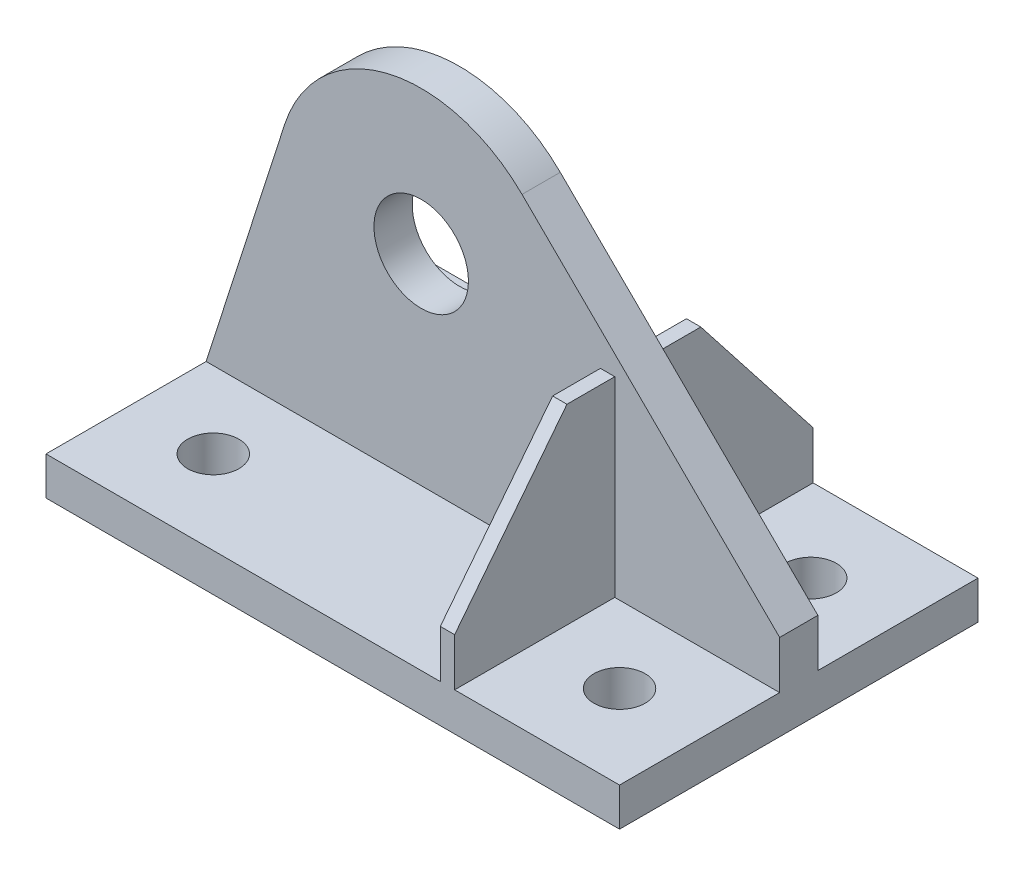
SolidWorks part; units mm, degrees
ref_plane "前视基准面" through (0, 0, 0) normal (0, 0, 1) x (1, 0, 0)
ref_plane "上视基准面" through (0, 0, 0) normal (0, 1, 0) x (1, 0, 0)
ref_plane "右视基准面" through (0, 0, 0) normal (1, 0, 0) x (0, 0, -1)
sketch "草图1" plane through (0, 0, 0) normal (0, 1, 0) x (1, 0, 0)
  line L1 (0, 0) -> (240, 0)
  line L2 (0, 0) -> (0, 150)
  line L3 (0, 150) -> (240, 150)
  line L4 (240, 0) -> (240, 150)
  dimension "D1" = 240
  dimension "D2" = 150
extrude "凸台-拉伸1" add sketch "草图1" along normal blind 16
sketch "草图2" plane through (0, 16, 0) normal (0, 1, 0) x (1, 0, 0)
  line L0 (0, 0) -> (240, 0) construction
  line L1 (0, 150) -> (0, 0) construction
  circle A0 centre (35, 35) radius 10.7283
  dimension "D1" = 35
  dimension "D2" = 35
extrude "切除-拉伸1" cut sketch "草图2" against normal through all
pattern_linear "阵列(线性)1" count 2 spacing 170 along (1, 0, 0) count 2 spacing 80 along (0, 0, -1) of "切除-拉伸1"
sketch "草图3" plane through (0, 16, 0) normal (0, 1, 0) x (1, 0, 0)
  line L0 (240, 150) -> (0, 150) construction
  line L1 (165, 150) -> (171, 150)
  line L2 (165, 150) -> (165, 0)
  line L3 (165, 0) -> (171, 0)
  line L4 (171, 150) -> (171, 0)
  line L5 (0, 0) -> (240, 0) construction
  line L6 (0, 150) -> (0, 0) construction
  dimension "D1" = 6
  dimension "D2" = 165
extrude "凸台-拉伸2" add sketch "草图3" along normal blind 80
sketch "草图4" plane through (165, 0, 0) normal (-1, 0, 0) x (0, 0, 1)
  line L0 (0, 96) -> (-47, 96)
  line L1 (-150, 96) -> (0, 96) construction
  line L2 (-47, 96) -> (0, 36)
  line L3 (0, 96) -> (0, 16) construction
  line L4 (-150, 96) -> (-103, 96)
  line L5 (-103, 96) -> (-150, 36)
  line L6 (-150, 96) -> (-150, 16) construction
  line L7 (-150, 36) -> (-150, 96)
  line L8 (0, 96) -> (0, 36)
  dimension "D1" = 60
  dimension "D2" = 47
  dimension "D3" = 60
  dimension "D4" = 47
extrude "切除-拉伸2" cut sketch "草图4" against normal through all
sketch "草图7" plane through (0, 16, 0) normal (0, 1, 0) x (1, 0, 0)
  line L0 (0, 75) -> (240, 75) construction
  line L1 (0, 150) -> (0, 0) construction
  line L2 (240, 0) -> (240, 150) construction
  line L4 (0, 83) -> (240, 83)
  line L5 (0, 83) -> (0, 67)
  line L6 (0, 67) -> (240, 67)
  line L7 (240, 83) -> (240, 67)
  dimension "D1" = 8
  dimension "D2" = 8
extrude "凸台-拉伸3" add sketch "草图7" along normal blind 144
sketch "草图12" plane through (0, 0, -67) normal (0, 0, 1) x (1, 0, 0)
  line L0 (0, 160) -> (240, 160) construction
  line L1 (0, 16) -> (165, 16) construction
  line L2 (0, 160) -> (0, 16) construction
  line L3 (32.8745, 118.3488) -> (0, 16)
  line L4 (0, 16) -> (0, 160)
  line L5 (0, 160) -> (90, 160)
  arc A0 (90, 160) -> (32.8745, 118.3488) centre (90, 100) ccw
  dimension "D3" = 60
  dimension "D1" = 84
  dimension "D2" = 90
extrude "切除-拉伸4" cut sketch "草图12" against normal through all
sketch "草图14" plane through (0, 0, -67) normal (0, 0, 1) x (1, 0, 0)
  line L0 (0, 16) -> (165, 16) construction
  line L1 (90, 160) -> (240, 160) construction
  line L2 (132.1986, 142.653) -> (240, 36)
  line L3 (240, 160) -> (240, 16) construction
  line L4 (240, 36) -> (240, 160)
  line L5 (240, 160) -> (90, 160)
  arc A0 (90, 160) -> (132.1986, 142.653) centre (90, 100) cw
  dimension "D1" = 84
  dimension "D2" = 90
  dimension "D3" = 20
  dimension "D4" = 150
extrude "切除-拉伸5" cut sketch "草图14" against normal through all
sketch "草图15" plane through (0, 0, -67) normal (0, 0, 1) x (1, 0, 0)
  line L0 (0, 16) -> (165, 16) construction
  circle A0 centre (90, 100) radius 19.7662
  dimension "D1" = 90
  dimension "D2" = 84
extrude "切除-拉伸6" cut sketch "草图15" against normal through all
